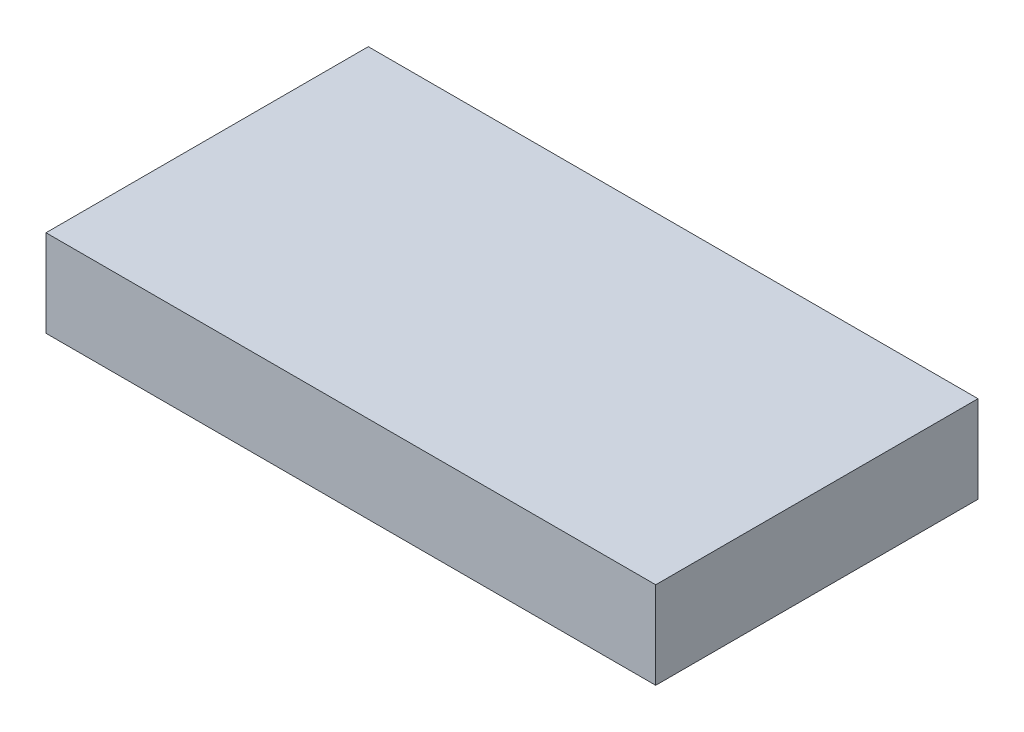
SolidWorks part; units mm, degrees
ref_plane "Front Plane" through (0, 0, 0) normal (0, 0, 1) x (1, 0, 0)
ref_plane "Top Plane" through (0, 0, 0) normal (0, 1, 0) x (1, 0, 0)
ref_plane "Right Plane" through (0, 0, 0) normal (1, 0, 0) x (0, 0, -1)
sketch "Sketch1" plane through (0, 0, 0) normal (0, 1, 0) x (1, 0, 0)
  line L1 (0, 0) -> (140, 0)
  line L2 (0, 0) -> (0, 74)
  line L3 (0, 74) -> (140, 74)
  line L4 (140, 0) -> (140, 74)
  dimension "D1" = 140
  dimension "D2" = 74
extrude "Boss-Extrude1" add sketch "Sketch1" along normal blind 20
